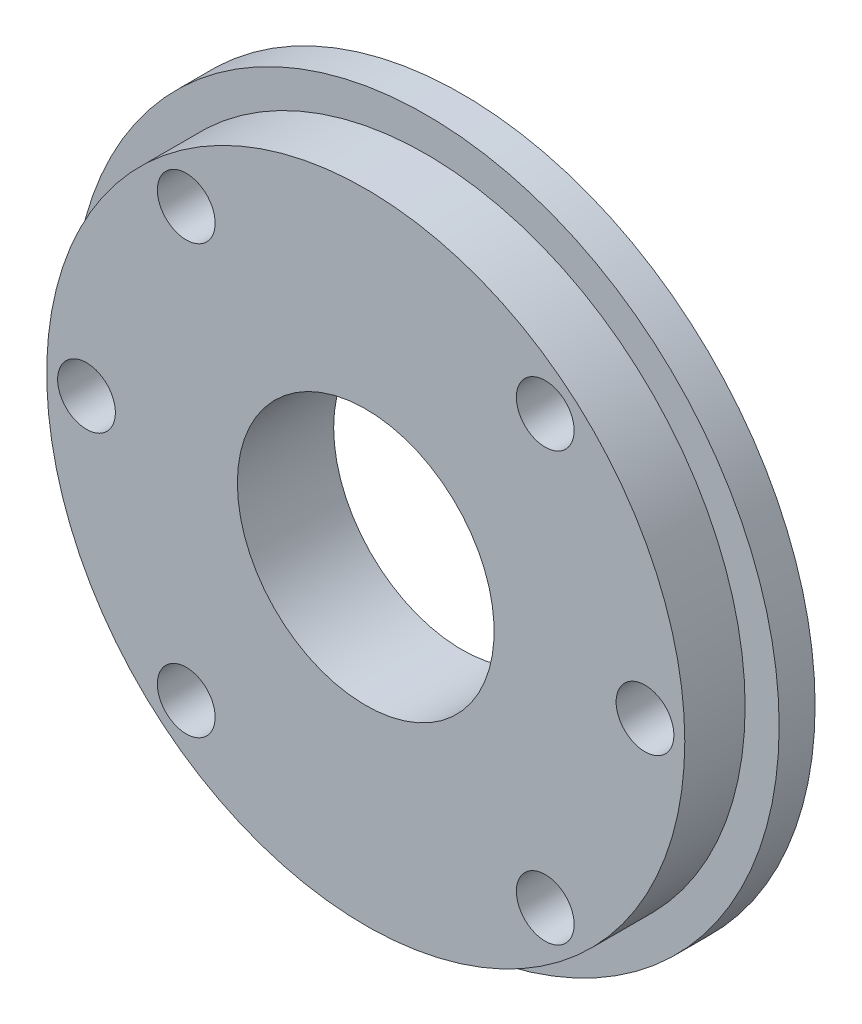
SolidWorks part; units mm, degrees
material "ABS"
ref_plane "前视基准面" through (0, 0, 0) normal (0, 0, 1) x (1, 0, 0)
ref_plane "上视基准面" through (0, 0, 0) normal (0, 1, 0) x (1, 0, 0)
ref_plane "右视基准面" through (0, 0, 0) normal (1, 0, 0) x (0, 0, -1)
sketch "草图1" plane through (0, 0, 0) normal (0, 0, 1) x (1, 0, 0)
  line L0 (-21.75, 0) -> (21.75, 0) construction
  line L1 (0, 0) -> (-13.9806, -16.6615) construction
  line L2 (0, 0) -> (13.9806, 16.6615) construction
  line L3 (-13.9806, 16.6615) -> (0, 0) construction
  line L4 (0, 0) -> (13.9806, -16.6615) construction
  circle A0 centre (0, 0) radius 21.75 construction
  circle A1 centre (0, 0) radius 24.85
  circle A2 centre (-21.75, 0) radius 2.25
  circle A3 centre (-13.9806, 16.6615) radius 2.25
  circle A4 centre (-13.9806, -16.6615) radius 2.25
  circle A5 centre (13.9806, -16.6615) radius 2.25
  circle A6 centre (21.75, 0) radius 2.25
  circle A7 centre (13.9806, 16.6615) radius 2.25
  dimension "D1" = 49.7
  dimension "D2" = 43.5
  dimension "D7" = 4.5
  dimension "D3" = 50
extrude "凸台-拉伸1" add sketch "草图1" along normal blind 7.5
sketch "草图3" plane through (0, 0, 0) normal (0, 0, 1) x (1, 0, 0)
  circle A0 centre (0, 0) radius 24.85 construction
  circle A1 centre (0, 0) radius 24.85
  circle A2 centre (0, 0) radius 27.5
  dimension "D1" = 55
extrude "凸台-拉伸2" add sketch "草图3" along normal blind 2.8
sketch "草图4" plane through (0, 0, 0) normal (0, 0, -1) x (-1, 0, 0)
  circle A0 centre (0, 0) radius 10
  dimension "D1" = 20
extrude "切除-拉伸1" cut sketch "草图4" against normal through all
